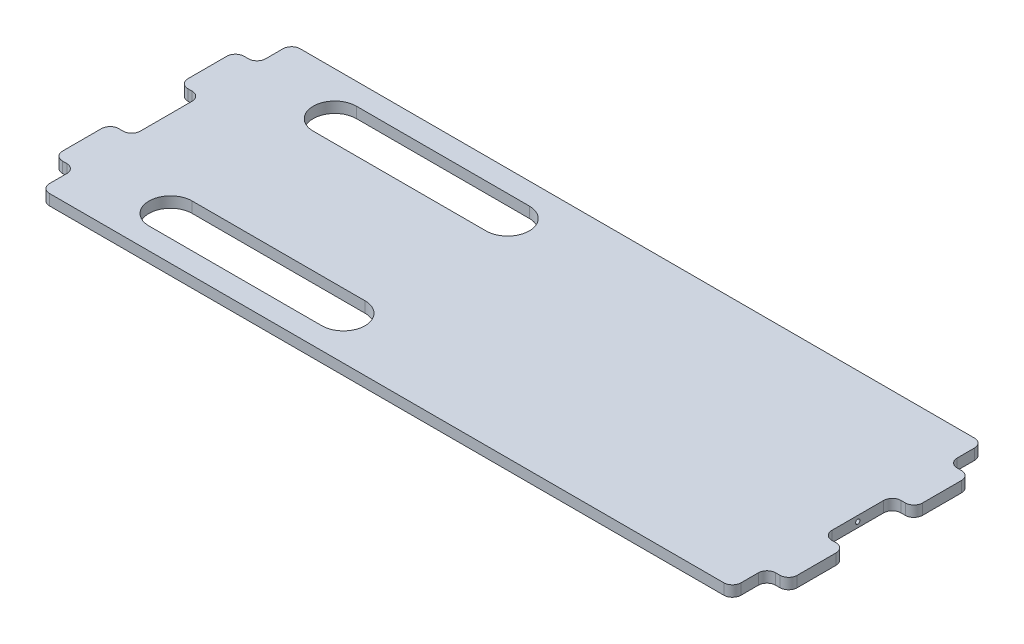
SolidWorks part; units mm, degrees
ref_plane "Front Plane" through (0, 0, 0) normal (0, 0, 1) x (1, 0, 0)
ref_plane "Top Plane" through (0, 0, 0) normal (0, 1, 0) x (1, 0, 0)
ref_plane "Right Plane" through (0, 0, 0) normal (1, 0, 0) x (0, 0, -1)
sketch "Sketch1" plane through (0, 0, 0) normal (0, 1, 0) x (1, 0, 0)
  line L0 (-76.2, -24.13) -> (-25.4, -24.13) construction
  line L1 (-101.6, 36.83) -> (101.6, 36.83)
  line L3 (-101.6, -36.83) -> (101.6, -36.83)
  line L5 (-101.6, 0) -> (0, 0) construction
  line L6 (-50.8, 0) -> (-50.8, -36.83) construction
  line L7 (-76.2, -17.78) -> (-25.4, -17.78)
  line L8 (-76.2, -30.48) -> (-25.4, -30.48)
  line L9 (-76.2, 24.13) -> (-25.4, 24.13) construction
  line L10 (-76.2, 17.78) -> (-25.4, 17.78)
  line L11 (-76.2, 30.48) -> (-25.4, 30.48)
  line L12 (0, 36.83) -> (0, -36.83) construction
  line L13 (-101.6, 36.83) -> (-101.6, 26.67)
  line L14 (-101.6, 26.67) -> (-107.95, 26.67)
  line L15 (-107.95, 26.67) -> (-107.95, 10.16)
  line L16 (-107.95, 10.16) -> (-101.6, 10.16)
  line L17 (-86.2421, 36.83) -> (-86.2421, 0) construction
  line L18 (-101.6, 10.16) -> (-101.6, -10.16)
  line L19 (-107.95, -10.16) -> (-101.6, -10.16)
  line L20 (-107.95, -26.67) -> (-107.95, -10.16)
  line L21 (-101.6, -26.67) -> (-107.95, -26.67)
  line L22 (-101.6, -36.83) -> (-101.6, -26.67)
  line L23 (101.6, -36.83) -> (101.6, -26.67)
  line L24 (101.6, -26.67) -> (107.95, -26.67)
  line L25 (107.95, -26.67) -> (107.95, -10.16)
  line L26 (107.95, -10.16) -> (101.6, -10.16)
  line L27 (101.6, 10.16) -> (101.6, -10.16)
  line L28 (107.95, 10.16) -> (101.6, 10.16)
  line L29 (107.95, 26.67) -> (107.95, 10.16)
  line L30 (101.6, 26.67) -> (107.95, 26.67)
  line L31 (101.6, 36.83) -> (101.6, 26.67)
  arc A0 (-76.2, -17.78) -> (-76.2, -30.48) centre (-76.2, -24.13) ccw
  arc A1 (-25.4, -30.48) -> (-25.4, -17.78) centre (-25.4, -24.13) ccw
  arc A2 (-76.2, 17.78) -> (-76.2, 30.48) centre (-76.2, 24.13) cw
  arc A3 (-25.4, 30.48) -> (-25.4, 17.78) centre (-25.4, 24.13) cw
  point P0 (0, 0)
  point P8 (-50.8, -24.13)
  point P13 (-86.2421, 18.415)
  point P15 (0, 36.83)
  point P16 (0, -36.83)
  point P25 (-50.8, 24.13)
  point P30 (-107.95, 18.415)
  point P34 (0, 0)
  point P35 (-101.6, 26.5609)
  dimension "D4" = 6.35
  dimension "D1" = 73.66
  dimension "D2" = 203.2
  dimension "D3" = 50.8
  dimension "D5" = 12.7
  dimension "D6" = 6.35
  dimension "D7" = 16.51
extrude "Boss-Extrude1" add sketch "Sketch1" along normal blind 3.175
fillet "Fillet1" radius 2.54 20 edges at (-101.6, 1.5875, -36.83) (-101.6, 1.5875, -26.67) (-107.95, 1.5875, -26.67) (-107.95, 1.5875, 10.16) (-101.6, 1.5875, 10.16) (-107.95, 1.5875, -10.16) (-101.6, 1.5875, -10.16) (-101.6, 1.5875, 36.83) (-101.6, 1.5875, 26.67) (-107.95, 1.5875, 26.67) (101.6, 1.5875, 36.83) (107.95, 1.5875, 26.67) (101.6, 1.5875, 26.67) (107.95, 1.5875, 10.16) (101.6, 1.5875, 10.16) (107.95, 1.5875, -10.16) (101.6, 1.5875, -10.16) (107.95, 1.5875, -26.67) (101.6, 1.5875, -26.67) (101.6, 1.5875, -36.83)
sketch "Sketch3" plane through (-101.6, 0, 0) normal (-1, 0, 0) x (0, 0, 1)
  line L0 (0, 3.175) -> (0, 0) construction
  line L1 (-7.62, 3.175) -> (7.62, 3.175) construction
  circle A0 centre (0, 1.5875) radius 0.635
  dimension "D1" = 1.27
extrude "Cut-Extrude1" cut sketch "Sketch3" against normal through all
